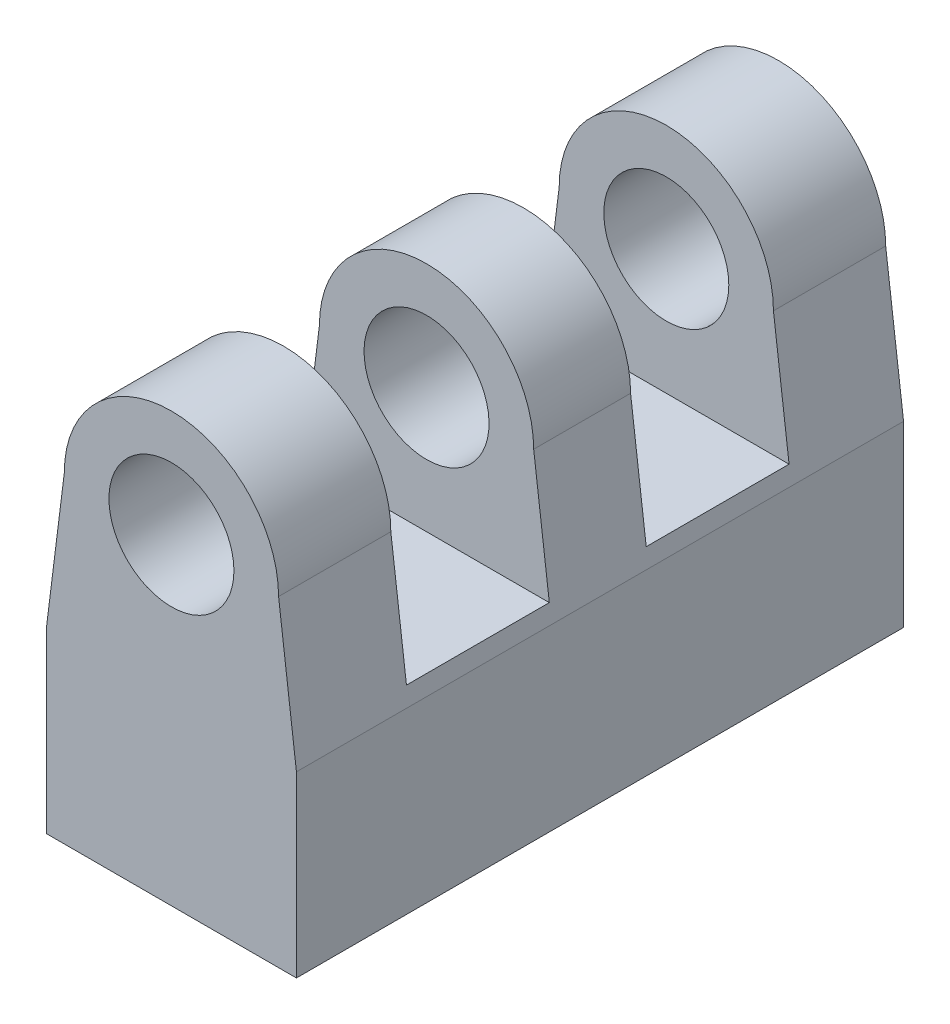
SolidWorks part; units mm, degrees
ref_plane "前视基准面" through (0, 0, 0) normal (0, 0, 1) x (1, 0, 0)
ref_plane "上视基准面" through (0, 0, 0) normal (0, 1, 0) x (1, 0, 0)
ref_plane "右视基准面" through (0, 0, 0) normal (1, 0, 0) x (0, 0, -1)
sketch "草图1" plane through (0, 0, 0) normal (0, 0, 1) x (1, 0, 0)
  line L0 (0, 0) -> (0, 13) construction
  line L2 (7, 5) -> (7, -5)
  line L3 (7, -5) -> (-7, -5)
  line L4 (-7, 5) -> (-7, -5)
  line L5 (7, 5) -> (-7, -5) construction
  line L6 (7, -5) -> (-7, 5) construction
  line L7 (0, 13) -> (0, 19) construction
  line L8 (-6, 13) -> (-7, 5)
  line L9 (6, 13) -> (7, 5)
  circle A0 centre (0, 13) radius 3.5
  arc A1 (6, 13) -> (-6, 13) centre (0, 13) ccw
  point P0 (0, 0)
  dimension "D4" = 7
  dimension "D5" = 12
  dimension "D1" = 14
  dimension "D2" = 10
  dimension "D3" = 13
extrude "凸台-拉伸2" add sketch "草图1" along normal blind 34
ref_plane "基准面1" through (7, 0, 0) normal (1, 0, 0) x (0, 0, -1)
sketch "草图3" plane through (7, 0, 0) normal (1, 0, 0) x (0, 0, -1)
  line L0 (-17, 27.3881) -> (-17, -17.3881) construction
  line L2 (-13.7136, 19) -> (-19.7136, 19)
  line L3 (0, 19) -> (-34, 19) construction
  line L4 (-19.7136, 19) -> (-27.7136, 19)
  line L5 (-19.7136, 19) -> (-19.7136, 6)
  line L6 (-27.7136, 19) -> (-27.7136, 6)
  line L7 (-19.7136, 6) -> (-27.7136, 6)
  line L8 (-6.2864, 19) -> (-6.2864, 6)
  line L9 (-14.2864, 6) -> (-6.2864, 6)
  line L10 (-14.2864, 19) -> (-14.2864, 6)
  line L11 (-14.2864, 19) -> (-6.2864, 19)
  point P3 (-17, 5)
  point P8 (-16.7136, 19)
  dimension "D1" = 8
  dimension "D2" = 13
  dimension "D3" = 6
extrude "切除-拉伸1" cut sketch "草图3" against normal through all both and the other way through all contours L7 L5 L4 L6 | L11 L2 L10 L9 L8
sketch "草图4" plane through (0, -5, 0) normal (0, -1, 0) x (1, 0, 0)
  line L0 (-7, 34) -> (-7, 0)
  line L1 (-7, 34) -> (6.9963, 34)
  line L3 (-7, 0) -> (6.9963, 0)
  line L4 (6.9963, 34) -> (6.9963, 0)
  line L5 (-0.0019, 34) -> (-0.0019, 17) construction
  circle A1 centre (-0.0019, 27) radius 5.05
  circle A2 centre (-0.0019, 7) radius 5.05
  dimension "D1" = 10.1
  dimension "D2" = 10.1
  dimension "D3" = 7
  dimension "D4" = 7
extrude "切除-拉伸3" cut sketch "草图4" against normal blind 10 contours A1 | A2
